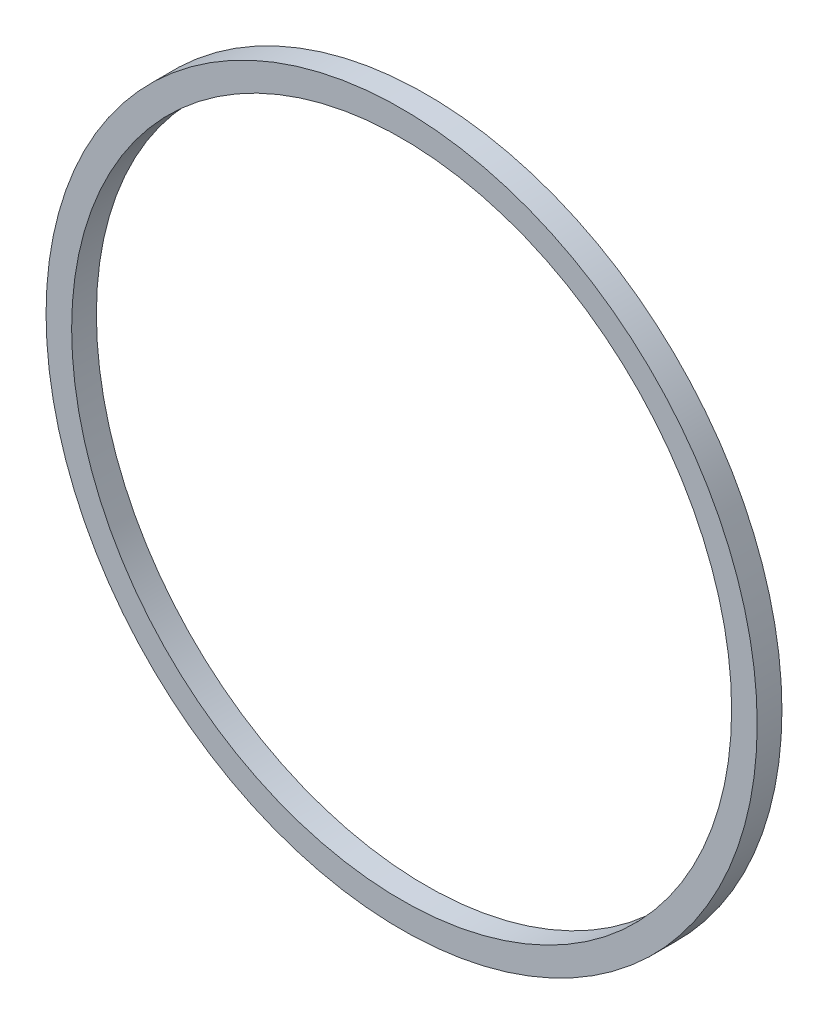
SolidWorks part; units mm, degrees
ref_plane "Front Plane" through (0, 0, 0) normal (0, 0, 1) x (1, 0, 0)
ref_plane "Top Plane" through (0, 0, 0) normal (0, 1, 0) x (1, 0, 0)
ref_plane "Right Plane" through (0, 0, 0) normal (1, 0, 0) x (0, 0, -1)
sketch "Sketch1" plane through (0, 0, 0) normal (0, 0, 1) x (1, 0, 0)
  circle A0 centre (0, 0) radius 1016
  dimension "D1" = 2032
extrude "Extrude-Thin1" add sketch "Sketch1" along normal blind 76.2 thin
